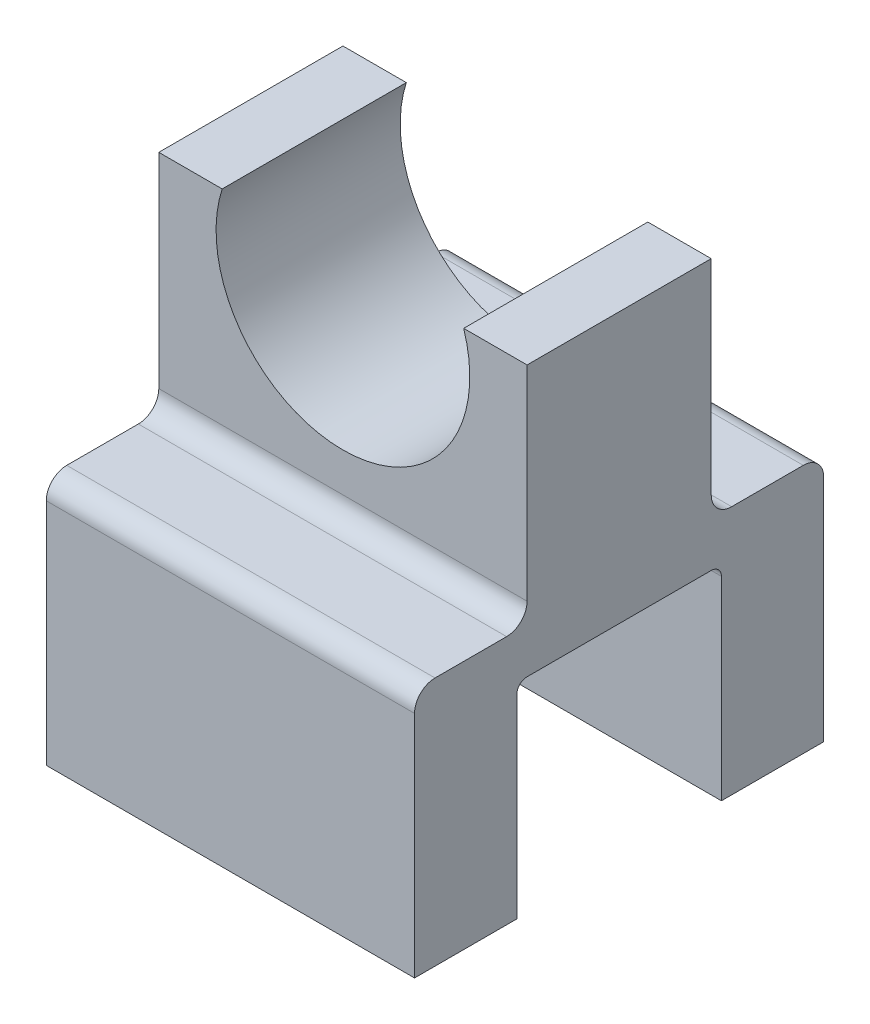
SolidWorks part; units mm, degrees
ref_plane "Front Plane" through (0, 0, 0) normal (0, 0, 1) x (1, 0, 0)
ref_plane "Top Plane" through (0, 0, 0) normal (0, 1, 0) x (1, 0, 0)
ref_plane "Right Plane" through (0, 0, 0) normal (1, 0, 0) x (0, 0, -1)
sketch "Sketch1" plane through (0, 0, 0) normal (0, 0, 1) x (1, 0, 0)
  line L0 (37.8503, 58.928) -> (45.72, 58.928)
  line L1 (0, 0) -> (45.72, 0)
  line L2 (0, 0) -> (0, 58.928)
  line L3 (0, 58.928) -> (7.8697, 58.928)
  line L4 (45.72, 0) -> (45.72, 58.928)
  arc A0 (7.8697, 58.928) -> (37.8503, 58.928) centre (22.86, 54.102) ccw
  dimension "D3" = 31.496
  dimension "D1" = 45.72
  dimension "D2" = 22.86
  dimension "D4" = 54.102
  dimension "D5" = 58.928
extrude "Boss-Extrude1" add sketch "Sketch1" along normal blind 50.8
sketch "Sketch2" plane through (45.72, 0, 0) normal (1, 0, 0) x (0, 0, -1)
  line L0 (-50.8, 0) -> (0, 0) construction
  line L1 (-38.1, 0) -> (-12.7, 0)
  line L2 (-38.1, 0) -> (-38.1, 25.4)
  line L3 (-38.1, 25.4) -> (-12.7, 25.4)
  line L4 (-12.7, 0) -> (-12.7, 25.4)
  line L5 (-50.8, 0) -> (-50.8, 58.928) construction
  dimension "D1" = 25.4
  dimension "D2" = 25.4
  dimension "D3" = 12.7
extrude "Cut-Extrude1" cut sketch "Sketch2" against normal through all
fillet "Fillet1" radius 1.27 2 edges at (22.86, 25.4, 38.1) (22.86, 25.4, 12.7)
sketch "Sketch4" plane through (0, 0, 0) normal (-1, 0, 0) x (0, 0, 1)
  line L1 (50.8, 58.928) -> (36.83, 58.928)
  line L2 (50.8, 58.928) -> (50.8, 30.988)
  line L3 (50.8, 30.988) -> (36.83, 30.988)
  line L4 (36.83, 58.928) -> (36.83, 30.988)
  line L5 (0, 58.928) -> (13.97, 58.928)
  line L6 (0, 58.928) -> (0, 30.988)
  line L7 (0, 30.988) -> (13.97, 30.988)
  line L8 (13.97, 58.928) -> (13.97, 30.988)
  dimension "D1" = 22.86
  dimension "D2" = 27.94
extrude "Cut-Extrude2" cut sketch "Sketch4" against normal through all
fillet "Fillet2" radius 2.54 4 edges at (22.86, 30.988, 0) (22.86, 30.988, 50.8) (22.86, 30.988, 36.83) (22.86, 30.988, 13.97)
